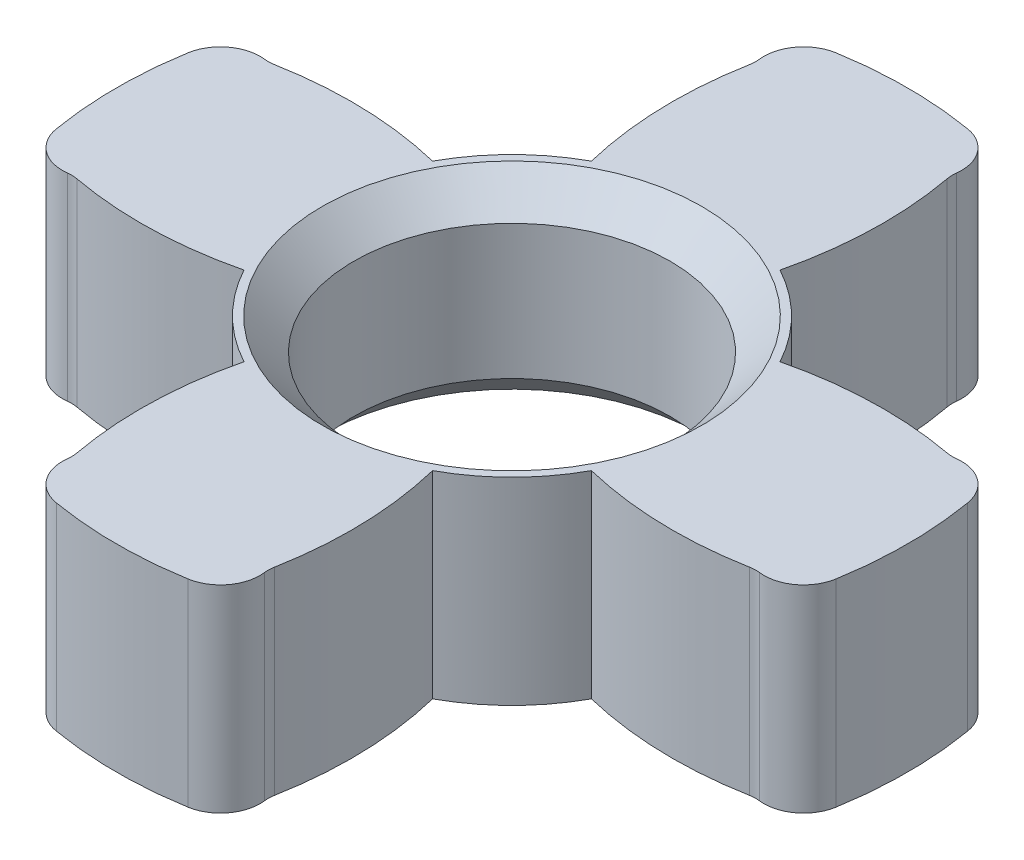
SolidWorks part; units mm, degrees
ref_plane "前视基准面" through (0, 0, 0) normal (0, 0, 1) x (1, 0, 0)
ref_plane "上视基准面" through (0, 0, 0) normal (0, 1, 0) x (1, 0, 0)
ref_plane "右视基准面" through (0, 0, 0) normal (1, 0, 0) x (0, 0, -1)
sketch "草图1" plane through (0, 0, 0) normal (0, 1, 0) x (1, 0, 0)
  line L0 (0, 0.3146) -> (0, 50000.3146) construction
  line L1 (0, 0) -> (50000, 0) construction
  line L2 (-2.5, 8.8741) -> (-2.5, 8.5082) construction
  line L3 (2.5, 8.8741) -> (2.5, 8.5082) construction
  line L4 (8.8741, -2.5) -> (8.5082, -2.5) construction
  line L5 (8.8741, 2.5) -> (8.5082, 2.5) construction
  line L6 (-2.5, -8.8741) -> (-2.5, -8.5082) construction
  line L7 (2.5, -8.8741) -> (2.5, -8.5082) construction
  line L8 (-8.8741, 2.5) -> (-8.5082, 2.5) construction
  line L9 (-8.8741, -2.5) -> (-8.5082, -2.5) construction
  arc A0 (-9.8601, 1.6667) -> (-9.8601, -1.6667) centre (0, 0) ccw
  arc A1 (-4.3943, -2.3855) -> (-2.3855, -4.3943) centre (0, 0) ccw
  arc A2 (0, 0) -> (-2.5, 8.5082) centre (7.1351, 6.7179) cw construction
  arc A3 (-2.5, 8.5082) -> (-2.4925, 8.752) centre (-3.2865, 8.6544) ccw
  arc A4 (-2.4925, 8.752) -> (-1.6667, 9.8601) centre (-1.5, 8.8741) cw
  arc A5 (-2.3855, 4.3943) -> (-2.5, 8.5082) centre (7.1351, 6.7179) cw
  arc A6 (2.4925, 8.752) -> (1.6667, 9.8601) centre (1.5, 8.8741) ccw
  arc A7 (2.5, 8.5082) -> (2.4925, 8.752) centre (3.2865, 8.6544) cw
  arc A8 (2.3855, 4.3943) -> (2.5, 8.5082) centre (-7.1351, 6.7179) ccw
  arc A9 (4.3943, -2.3855) -> (8.5082, -2.5) centre (6.7179, 7.1351) ccw
  arc A10 (8.752, -2.4925) -> (9.8601, -1.6667) centre (8.8741, -1.5) ccw
  arc A11 (8.5082, -2.5) -> (8.752, -2.4925) centre (8.6544, -3.2865) cw
  arc A12 (8.752, 2.4925) -> (9.8601, 1.6667) centre (8.8741, 1.5) cw
  arc A13 (8.5082, 2.5) -> (8.752, 2.4925) centre (8.6544, 3.2865) ccw
  arc A14 (4.3943, 2.3855) -> (8.5082, 2.5) centre (6.7179, -7.1351) cw
  arc A15 (-2.3855, -4.3943) -> (-2.5, -8.5082) centre (7.1351, -6.7179) ccw
  arc A16 (-2.4925, -8.752) -> (-1.6667, -9.8601) centre (-1.5, -8.8741) ccw
  arc A17 (-2.5, -8.5082) -> (-2.4925, -8.752) centre (-3.2865, -8.6544) cw
  arc A18 (2.4925, -8.752) -> (1.6667, -9.8601) centre (1.5, -8.8741) cw
  arc A19 (2.5, -8.5082) -> (2.4925, -8.752) centre (3.2865, -8.6544) ccw
  arc A20 (2.3855, -4.3943) -> (2.5, -8.5082) centre (-7.1351, -6.7179) cw
  arc A21 (-4.3943, 2.3855) -> (-8.5082, 2.5) centre (-6.7179, -7.1351) ccw
  arc A22 (-8.752, 2.4925) -> (-9.8601, 1.6667) centre (-8.8741, 1.5) ccw
  arc A23 (-8.5082, 2.5) -> (-8.752, 2.4925) centre (-8.6544, 3.2865) cw
  arc A24 (-8.752, -2.4925) -> (-9.8601, -1.6667) centre (-8.8741, -1.5) cw
  arc A25 (-8.5082, -2.5) -> (-8.752, -2.4925) centre (-8.6544, -3.2865) ccw
  arc A26 (-4.3943, -2.3855) -> (-8.5082, -2.5) centre (-6.7179, 7.1351) cw
  arc A27 (1.6667, 9.8601) -> (-1.6667, 9.8601) centre (0, 0) ccw
  arc A28 (9.8601, -1.6667) -> (9.8601, 1.6667) centre (0, 0) ccw
  arc A29 (-1.6667, -9.8601) -> (1.6667, -9.8601) centre (0, 0) ccw
  arc A30 (-2.3855, 4.3943) -> (-4.3943, 2.3855) centre (0, 0) ccw
  arc A31 (4.3943, 2.3855) -> (2.3855, 4.3943) centre (0, 0) ccw
  arc A32 (2.3855, -4.3943) -> (4.3943, -2.3855) centre (0, 0) ccw
  point P70 (0, 0)
  point P81 (0, 0)
  dimension "D1" = 20
  dimension "D2" = 10
  dimension "D3" = 9.8
  dimension "D4" = 0.8
  dimension "D5" = 1
  dimension "D8" = 4
  dimension "D6" = 5
  dimension "D7" = 4
extrude "凸台-拉伸1" add sketch "草图1" along normal mid plane 5
sketch "草图4" plane through (0, 2.5, 0) normal (0, 1, 0) x (1, 0, 0)
  circle A0 centre (0, 0) radius 4
  dimension "D1" = 8
extrude "切除-拉伸1" cut sketch "草图4" against normal mid plane 12
chamfer "倒角1" distance 0.8 angle 45 1 edges at (0, 2.5, -4)
chamfer "倒角2" distance 0.8 angle 45 1 edges at (0, -2.5, -4)
